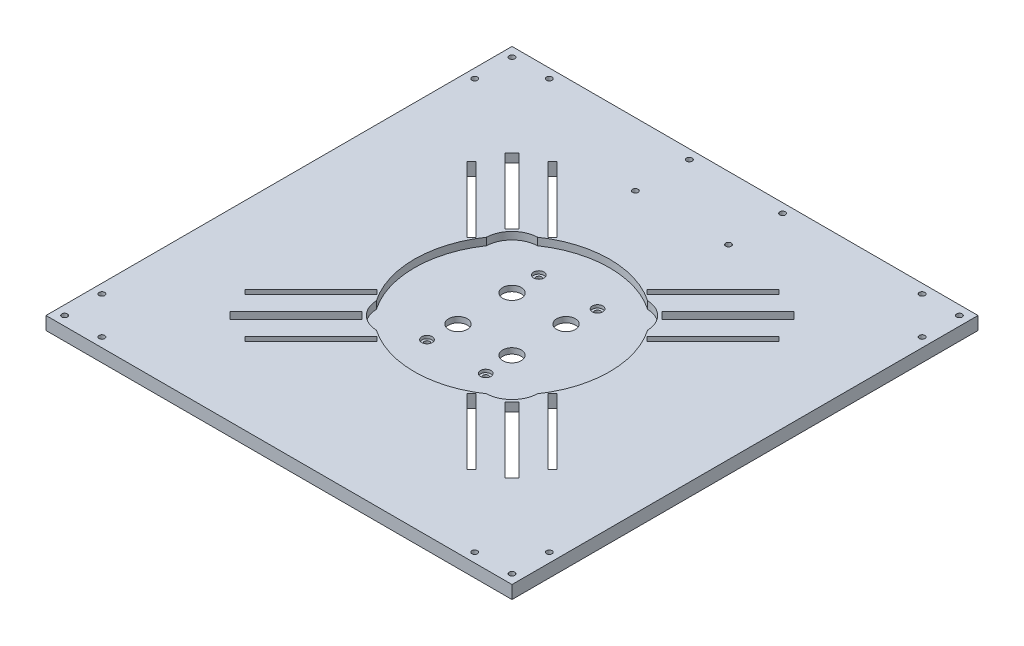
SolidWorks part; units mm, degrees
ref_plane "Front Plane" through (0, 0, 0) normal (0, 0, 1) x (1, 0, 0)
ref_plane "Top Plane" through (0, 0, 0) normal (0, 1, 0) x (1, 0, 0)
ref_plane "Right Plane" through (0, 0, 0) normal (1, 0, 0) x (0, 0, -1)
sketch "Sketch1" plane through (0, 0, 0) normal (0, 1, 0) x (1, 0, 0)
  line L1 (-125, 125) -> (125, 125)
  line L2 (-125, 125) -> (-125, -125)
  line L3 (-125, -125) -> (125, -125)
  line L4 (125, 125) -> (125, -125)
  line L5 (-125, 125) -> (125, -125) construction
  line L6 (-125, -125) -> (125, 125) construction
  point P0 (0, 0)
  dimension "D1" = 250
  dimension "D2" = 250
extrude "Boss-Extrude1" add sketch "Sketch1" along normal blind 7
sketch "Sketch4" plane through (0, 7, 0) normal (0, 1, 0) x (1, 0, 0)
  circle A1 centre (0, 0) radius 14 construction
  circle A2 centre (29, 0) radius 14 construction
  circle A3 centre (-29, 0) radius 14 construction
  circle A5 centre (0, -29) radius 14 construction
  circle A8 centre (0, 29) radius 14 construction
  arc A22 (-26.0405, 42.6836) -> (-42.6836, 26.0405) centre (-29, 29) ccw [skipped]
  arc A30 (42.6836, 26.0405) -> (26.0405, 42.6836) centre (29, 29) ccw [skipped]
  arc A32 (-29.5084, 43.2409) -> (-43.2409, 29.5084) centre (-29, 29) ccw
  arc A34 (-43.2409, -29.5084) -> (-29.5084, -43.2409) centre (-29, -29) ccw
  arc A36 (29.5084, -43.2409) -> (43.2409, -29.5084) centre (29, -29) ccw
  arc A38 (43.2409, 29.5084) -> (29.5084, 43.2409) centre (29, 29) ccw
  arc A39 (29.5084, 43.2409) -> (-29.5084, 43.2409) centre (0, 0) ccw
  arc A40 (-43.2409, 29.5084) -> (-43.2409, -29.5084) centre (0, 0) ccw
  arc A41 (-29.5084, -43.2409) -> (29.5084, -43.2409) centre (0, 0) ccw
  arc A42 (43.2409, -29.5084) -> (43.2409, 29.5084) centre (0, 0) ccw
  dimension "D1" = 104.7
  dimension "D2" = 28
  dimension "D3" = 29
  dimension "D4" = 29
  dimension "D7" = 2
extrude "Cut-Extrude2" cut sketch "Sketch4" against normal blind 4
sketch "Sketch5" plane through (0, 7, 0) normal (0, 1, 0) x (1, 0, 0)
  line L2 (-40.2278, 40.2278) -> (-38.354, 42.1016)
  line L3 (-40.2278, 40.2278) -> (-42.1016, 38.354)
  line L4 (-38.354, 42.1016) -> (-73.7093, 77.457)
  line L5 (-42.1016, 38.354) -> (-77.457, 73.7093)
  line L6 (-73.7093, 77.457) -> (-77.457, 73.7093)
  dimension "D2" = 2.65
  dimension "D3" = 50
extrude "Cut-Extrude3" cut sketch "Sketch5" against normal through all
sketch "Sketch6" plane through (0, 7, 0) normal (0, 1, 0) x (1, 0, 0)
  line L0 (-26.5424, 45.9878) -> (-61.8977, 81.3432)
  line L1 (-26.5424, 45.9878) -> (-24.1382, 48.392)
  line L2 (-61.8977, 81.3432) -> (-59.4936, 83.7473)
  line L3 (-24.1382, 48.392) -> (-59.4936, 83.7473)
  line L4 (-42.1016, 38.354) -> (-38.354, 42.1016) construction
  line L5 (-38.354, 42.1016) -> (-73.7093, 77.457) construction
  line L6 (-75.5831, 75.5831) -> (-40.2278, 40.2278) construction
  line L7 (-73.7093, 77.457) -> (-77.457, 73.7093) construction
  line L8 (-81.3432, 61.8977) -> (-83.7473, 59.4936)
  line L9 (-45.9878, 26.5424) -> (-48.392, 24.1382)
  line L10 (-48.392, 24.1382) -> (-83.7473, 59.4936)
  line L11 (-45.9878, 26.5424) -> (-81.3432, 61.8977)
  dimension "D1" = 3.4
  dimension "D2" = 11.1
extrude "Cut-Extrude4" cut sketch "Sketch6" against normal through all contours L11 L8 L10 L9
sketch "Sketch7" plane through (0, 0, 0) normal (0, -1, 0) x (1, 0, 0)
  line L0 (-90.8353, -74.5719) -> (-41.3379, -25.0744)
  line L1 (-90.8353, -74.5719) -> (-74.5719, -90.8353)
  line L2 (-41.3379, -25.0744) -> (-25.0744, -41.3379)
  line L3 (-74.5719, -90.8353) -> (-25.0744, -41.3379)
  line L4 (-42.1016, -38.354) -> (-38.354, -42.1016) construction
  line L6 (-38.354, -42.1016) -> (-73.7093, -77.457) construction
  dimension "D1" = 23
  dimension "D2" = 8.85
  dimension "D3" = 70
extrude "Cut-Extrude5" cut sketch "Sketch7" against normal blind 2.3
pattern_circular "CirPattern1" count 4 over 360 about axis through (0, 0, 0) along (0, 1, 0) of "Cut-Extrude3", "Cut-Extrude4", "Cut-Extrude5"
sketch "Sketch8" plane through (0, 7, 0) normal (0, 1, 0) x (1, 0, 0)
  line L0 (0, 29) -> (29, 0) construction
  circle A1 centre (0, 0) radius 14 construction
  circle A2 centre (29, 0) radius 14 construction
  circle A3 centre (-29, 0) radius 14 construction
  circle A8 centre (0, 29) radius 14 construction
  circle A43 centre (14.5, 14.5) radius 5
  circle A44 centre (-14.5, 14.5) radius 5
  circle A45 centre (-14.5, -14.5) radius 5
  circle A46 centre (14.5, -14.5) radius 5
  arc A47 (-26.0405, 42.6836) -> (-42.6836, 26.0405) centre (-29, 29) ccw [skipped]
  arc A48 (42.6836, 26.0405) -> (26.0405, 42.6836) centre (29, 29) ccw [skipped]
  dimension "D2" = 28
  dimension "D5" = 10
  dimension "D8" = 2
  dimension "D3" = 29
  dimension "D4" = 29
  dimension "D6" = 2
  dimension "D7" = 2
extrude "Cut-Extrude6" cut sketch "Sketch8" against normal through all
sketch "Sketch9" plane through (0, 3, 0) normal (0, 1, 0) x (1, 0, 0)
  line L0 (-15.6, -30) -> (15.9, -30) construction
  circle A0 centre (-15.6, -30) radius 1.5
  circle A1 centre (15.9, -30) radius 1.5
  dimension "D2" = 3
  dimension "D4" = 3
  dimension "D1" = 30
  dimension "D3" = 31.5
  dimension "D5" = 15.6
extrude "Cut-Extrude7" cut sketch "Sketch9" against normal through all
sketch "Sketch10" plane through (0, 3, 0) normal (0, 1, 0) x (1, 0, 0)
  circle A0 centre (-15.6, -30) radius 2.8
  circle A1 centre (15.9, -30) radius 2.8
  dimension "D1" = 5.6
  dimension "D2" = 5.6
extrude "Cut-Extrude8" cut sketch "Sketch10" against normal blind 1.6
ref_plane "Plane1" through (0, 0, 0) normal (0, 0, 1) x (1, 0, 0)
sketch "Sketch13" plane through (0, 7, 0) normal (0, 1, 0) x (1, 0, 0)
  line L0 (125, 125) -> (-125, 125) construction
  line L1 (0, -55) -> (0, 55) construction
  circle A0 centre (25.15, 120) radius 1.5
  dimension "D1" = 3
  dimension "D2" = 5
  dimension "D3" = 25.15
extrude "Cut-Extrude11" cut sketch "Sketch13" against normal through all
pattern_linear "LPattern1" count 2 spacing 50 along (-1, 0, 0) count 2 spacing 29 along (0, 0, 1) of "Cut-Extrude11"
mirror "Mirror1" about plane through (0, 0, 0) normal (0, 0, 1) of "Cut-Extrude7", "Cut-Extrude8"
sketch "Sketch14" plane through (0, 7, 0) normal (0, 1, 0) x (1, 0, 0)
  line L0 (125, -125) -> (125, 125) construction
  line L1 (-125, -125) -> (125, -125) construction
  circle A0 centre (120, -100) radius 1.5
  circle A1 centre (120, -120) radius 1.5
  circle A2 centre (100, -120) radius 1.5
  dimension "D1" = 3
  dimension "D2" = 3
  dimension "D3" = 3
  dimension "D4" = 5
  dimension "D5" = 5
  dimension "D6" = 20
  dimension "D7" = 20
extrude "Cut-Extrude12" cut sketch "Sketch14" against normal blind 10
mirror "Mirror2" about plane through (0, 0, 0) normal (1, 0, 0) of "Cut-Extrude12"
mirror "Mirror3" about plane through (0, 0, 0) normal (0, 0, 1) of "Mirror2", "Cut-Extrude12"
